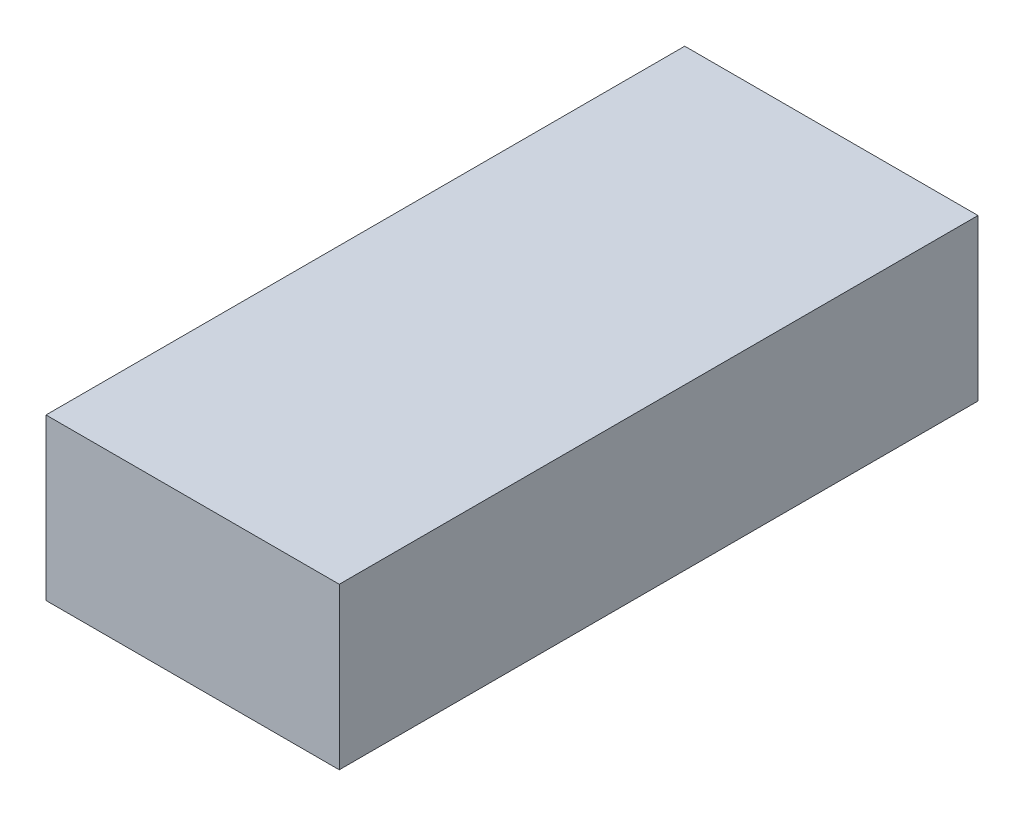
SolidWorks part; units mm, degrees
ref_plane "Front Plane" through (0, 0, 0) normal (0, 0, 1) x (1, 0, 0)
ref_plane "Top Plane" through (0, 0, 0) normal (0, 1, 0) x (1, 0, 0)
ref_plane "Right Plane" through (0, 0, 0) normal (1, 0, 0) x (0, 0, -1)
sketch "CurveSketch" plane through (0, 0, 0) normal (0, 0, 1) x (1, 0, 0)
  line L0 (-20.0525, -1.8635) -> (11.6665, -1.8635)
  line L1 (11.6665, -1.8635) -> (11.6665, 15.5175)
  line L2 (11.6665, 15.5175) -> (-20.0525, 15.5175)
  line L3 (-20.0525, 15.5175) -> (-20.0525, -1.8635)
extrude "CurveBoss" add sketch "CurveSketch" along normal blind 57.113 and the other way blind 11.971
